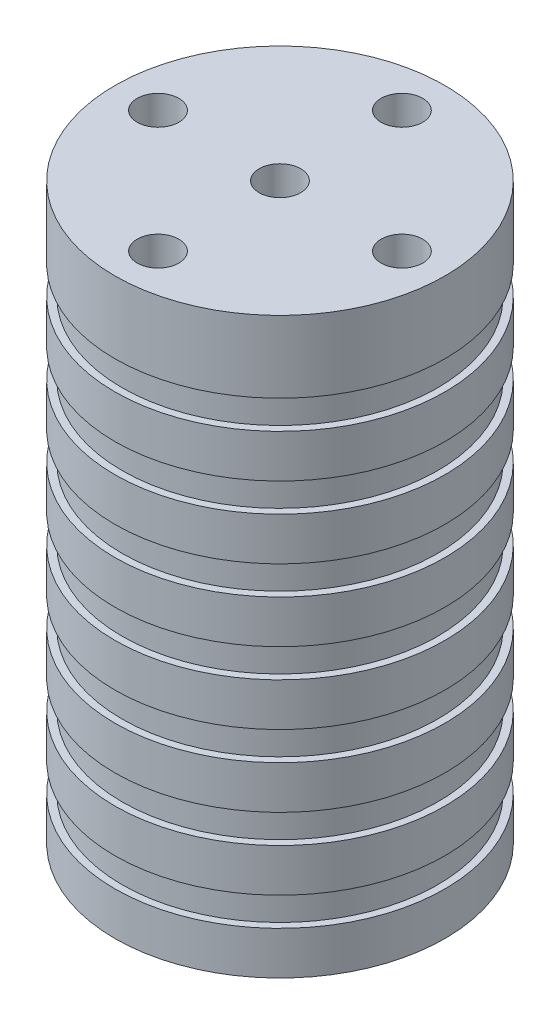
SolidWorks part; units mm, degrees
ref_plane "Front Plane" through (0, 0, 0) normal (0, 0, 1) x (1, 0, 0)
ref_plane "Top Plane" through (0, 0, 0) normal (0, 1, 0) x (1, 0, 0)
ref_plane "Right Plane" through (0, 0, 0) normal (1, 0, 0) x (0, 0, -1)
sketch "Sketch2" plane through (0, 0, 0) normal (0, 0, 1) x (1, 0, 0)
  line L0 (-11.5, 0) -> (11.5, 0)
  line L1 (11.5, 0) -> (11.5, -40)
  line L2 (11.5, -40) -> (5.5, -40)
  line L3 (5.5, -40) -> (5.5, -7)
  line L4 (0, 0) -> (0, -7)
  line L5 (-5.5, -40) -> (-5.5, -7)
  line L6 (-11.5, -40) -> (-5.5, -40)
  line L7 (-11.5, 0) -> (-11.5, -40)
  line L8 (-5.5, -7) -> (5.5, -7)
  point P4 (0, 0)
  point P13 (0, 0)
  point P14 (0, 0)
  point P15 (0, 0)
  point P16 (0, -7)
  dimension "D1" = 23
  dimension "D2" = 7
  dimension "D3" = 6
  dimension "D4" = 40
revolve "Revolve1" add sketch "Sketch2" angle 360 about L4
sketch "Sketch3" plane through (0, 0, 0) normal (0, 0, 1) x (1, 0, 0)
  line L0 (-11.5, -40) -> (11.5, -40) construction
  line L1 (-11.5, -40) -> (11.5, -40)
  line L2 (11.5, -40) -> (11.5, -37)
  line L3 (11.5, -40) -> (11.5, 0) construction
  line L4 (11.5, -37) -> (11, -37)
  line L5 (11, -37) -> (11, -35)
  line L6 (11, -35) -> (11.5, -35)
  line L7 (11.5, -37) -> (11.5, -35)
  dimension "D1" = 2
  dimension "D2" = 0.5
  dimension "D3" = 3
revolve "Cut-Revolve1" cut sketch "Sketch3" angle 360 about L4
pattern_linear "LPattern1" count 7 spacing 5 along (0, 1, 0) of "Cut-Revolve1"
sketch "Sketch4" plane through (0, 0, 0) normal (0, 1, 0) x (1, 0, 0)
  line L0 (-11.5, 0) -> (-11.5, 8.5) construction
  line L1 (-10.25, 0) -> (-10.25, 5.2142) construction
  line L2 (-11.5, 0) -> (-5.5, 0) construction
  circle A0 centre (0, 0) radius 8.5 construction
  circle A1 centre (0, 8.5) radius 1.75 construction
  circle A2 centre (8.5, 0) radius 1.75 construction
  circle A3 centre (0, -8.5) radius 1.75 construction
  circle A4 centre (-8.5, 0) radius 1.75 construction
  circle A5 centre (0, 0) radius 11.5 construction
  circle A7 centre (0, 0) radius 5.5
  circle A8 centre (0, 0) radius 5.5 construction
  point P0 (8.5, 0)
  point P14 (0, 0)
  point P19 (-8.5, 0)
  point P23 (0, 8.5)
  point P24 (0, 0)
  point P25 (0, -8.5)
  point P28 (0, 0)
  point P33 (0, 0)
  point P34 (0, 0)
  point P35 (0, 0)
  point P36 (0, 0)
  dimension "D3" = 3.5
  dimension "D4" = 0
  dimension "D1" = 4
hole_wizard "M3.5x0.6 Tapped Hole1" positions "Sketch4" profile "Sketch5" tap size "M3.5x0.6" standard "ANSI Metric"
sketch "Sketch5" plane through (8.5, 0, 0) normal (1, 0, 0) x (0, 0, 1)
  line L0 (0, 0) -> (0, 10.8712)
  line L1 (0, 10.8712) -> (1.45, 10)
  line L2 (1.45, 10) -> (1.45, 0)
  line L5 (1.45, 0) -> (0, 0)
  line L10 (0, 10.8712) -> (-1.45, 10) construction
  line L11 (0, -6.35) -> (0, 107.95) construction
  dimension "Tap Drill Dia." = 2.9
  dimension "Tap Drill Depth" = 10
  dimension "Drill Angle" = 118
cosmetic thread "Hole Thread1" parameters "D1"=7, "D2"=3.5
cosmetic thread "Hole Thread2" parameters "D1"=7, "D2"=3.5
cosmetic thread "Hole Thread3" parameters "D1"=7, "D2"=3.5
cosmetic thread "Hole Thread4" parameters "D1"=7, "D2"=3.5
cosmetic thread "Hole Thread5" parameters "D1"=7, "D2"=3.5
